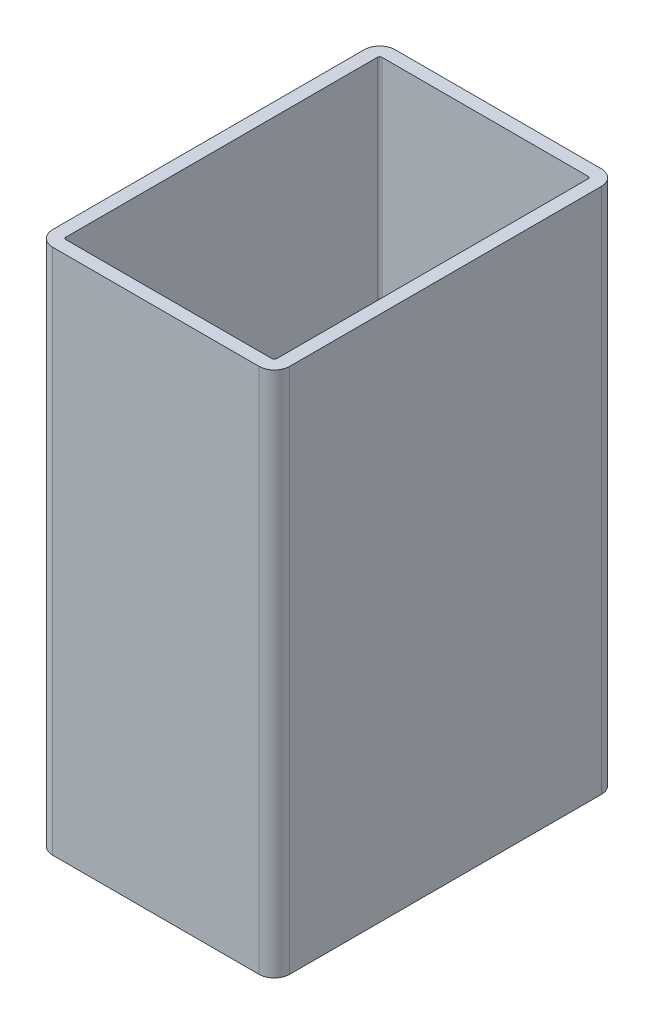
SolidWorks part; units mm, degrees
other "Weld Folder"
ref_plane "Front Plane" through (0, 0, 0) normal (0, 0, 1) x (1, 0, 0)
ref_plane "Top Plane" through (0, 0, 0) normal (0, 1, 0) x (1, 0, 0)
ref_plane "Right Plane" through (0, 0, 0) normal (1, 0, 0) x (0, 0, -1)
sketch "Sketch1" plane through (0, 0, 0) normal (0, 0, 1) x (1, 0, 0)
  line L0 (0, 0) -> (0, 400)
  dimension "D1" = 400
other "Rhs RHS90X50X5(1)"
ref_plane "Plane1" through (0, 0, 0) normal (0, 1, 0) x (-1, 0, 0)
sketch "Sketch115" plane through (0, 0, 0) normal (0, 1, 0) x (-1, 0, 0)
  line L0 (-78.3333, -120) -> (78.3333, -120)
  line L1 (-80, -118.3333) -> (-80, 118.3333)
  line L2 (78.3333, 120) -> (-78.3333, 120)
  line L3 (80, 118.3333) -> (80, -118.3333)
  line L4 (-78.3333, -130) -> (78.3333, -130)
  line L5 (-90, -118.3333) -> (-90, 118.3333)
  line L6 (78.3333, 130) -> (-78.3333, 130)
  line L7 (90, 118.3333) -> (90, -118.3333)
  line L8 (-90, 0) -> (-80, 0) construction
  line L9 (-80, 0) -> (80, 0) construction
  line L10 (80, 0) -> (90, 0) construction
  line L11 (0, 130) -> (0, 120) construction
  line L12 (0, 120) -> (0, -120) construction
  line L13 (0, -120) -> (0, -130) construction
  arc A0 (90, 118.3333) -> (78.3333, 130) centre (78.3333, 118.3333) ccw
  arc A1 (78.3333, -130) -> (90, -118.3333) centre (78.3333, -118.3333) ccw
  arc A2 (-90, -118.3333) -> (-78.3333, -130) centre (-78.3333, -118.3333) ccw
  arc A3 (-78.3333, 130) -> (-90, 118.3333) centre (-78.3333, 118.3333) ccw
  arc A4 (-78.3333, 120) -> (-80, 118.3333) centre (-78.3333, 118.3333) ccw
  arc A5 (80, 118.3333) -> (78.3333, 120) centre (78.3333, 118.3333) ccw
  arc A6 (78.3333, -120) -> (80, -118.3333) centre (78.3333, -118.3333) ccw
  arc A7 (-80, -118.3333) -> (-78.3333, -120) centre (-78.3333, -118.3333) ccw
  point P6 (90, -130)
  point P33 (-90, -130)
  point P34 (-322.3979, 111.0397)
  point P35 (-90, 130)
  point P36 (90, 130)
  point P37 (0, 0)
  point P38 (0, 0)
  dimension "Thickness" = 10
  dimension "V_leg" = 260
  dimension "H_leg" = 180
sketch "Sketch116" plane through (0, 0, 0) normal (0, -1, 0) x (1, 0, 0)
  line L0 (90, 118.3333) -> (90, -118.3333) construction
  line L1 (78.3333, -130) -> (-78.3333, -130) construction
  line L2 (-90, -118.3333) -> (-90, 118.3333) construction
  line L3 (-78.3333, 130) -> (78.3333, 130) construction
  line L4 (90, 118.3333) -> (90, -118.3333)
  line L5 (78.3333, -130) -> (-78.3333, -130)
  line L6 (-90, -118.3333) -> (-90, 118.3333)
  line L7 (-78.3333, 130) -> (78.3333, 130)
  arc A0 (78.3333, -130) -> (90, -118.3333) centre (78.3333, -118.3333) ccw construction
  arc A1 (90, 118.3333) -> (78.3333, 130) centre (78.3333, 118.3333) ccw construction
  arc A2 (-90, -118.3333) -> (-78.3333, -130) centre (-78.3333, -118.3333) ccw construction
  arc A3 (-78.3333, 130) -> (-90, 118.3333) centre (-78.3333, 118.3333) ccw construction
  arc A4 (78.3333, -130) -> (90, -118.3333) centre (78.3333, -118.3333) ccw
  arc A5 (90, 118.3333) -> (78.3333, 130) centre (78.3333, 118.3333) ccw
  arc A6 (-90, -118.3333) -> (-78.3333, -130) centre (-78.3333, -118.3333) ccw
  arc A7 (-78.3333, 130) -> (-90, 118.3333) centre (-78.3333, 118.3333) ccw
sketch "Sketch121" plane through (-90, 0, 0) normal (-1, 0, 0) x (0, 0, 1)
  line L0 (-118.3333, 400) -> (118.3333, 400) construction
  point P0 (0, 275)
  dimension "D1" = 125
